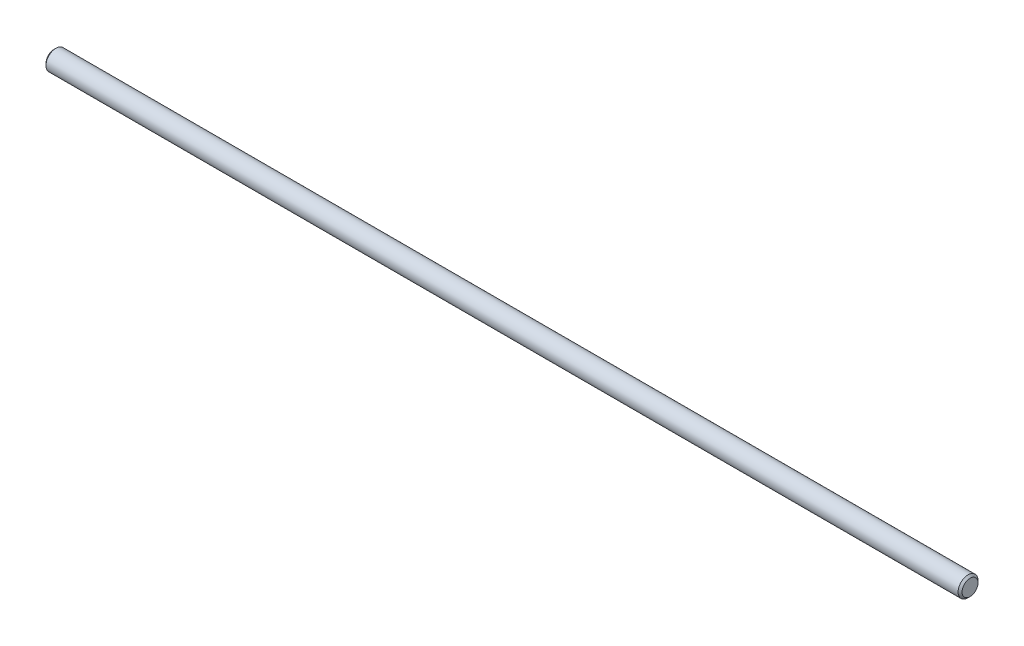
SolidWorks part; units mm, degrees
ref_plane "Front Plane" through (0, 0, 0) normal (0, 0, 1) x (1, 0, 0)
ref_plane "Top Plane" through (0, 0, 0) normal (0, 1, 0) x (1, 0, 0)
ref_plane "Right Plane" through (0, 0, 0) normal (1, 0, 0) x (0, 0, -1)
sketch "Sketch1" plane through (0, 0, 0) normal (1, 0, 0) x (0, 0, -1)
  circle A0 centre (0, 0) radius 5
  dimension "D1" = 10
extrude "Boss-Extrude1" add sketch "Sketch1" along normal mid plane 460
chamfer "Chamfer1" distance 1 angle 45 2 edges at (230, 0, -5) (-230, 0, -5)
